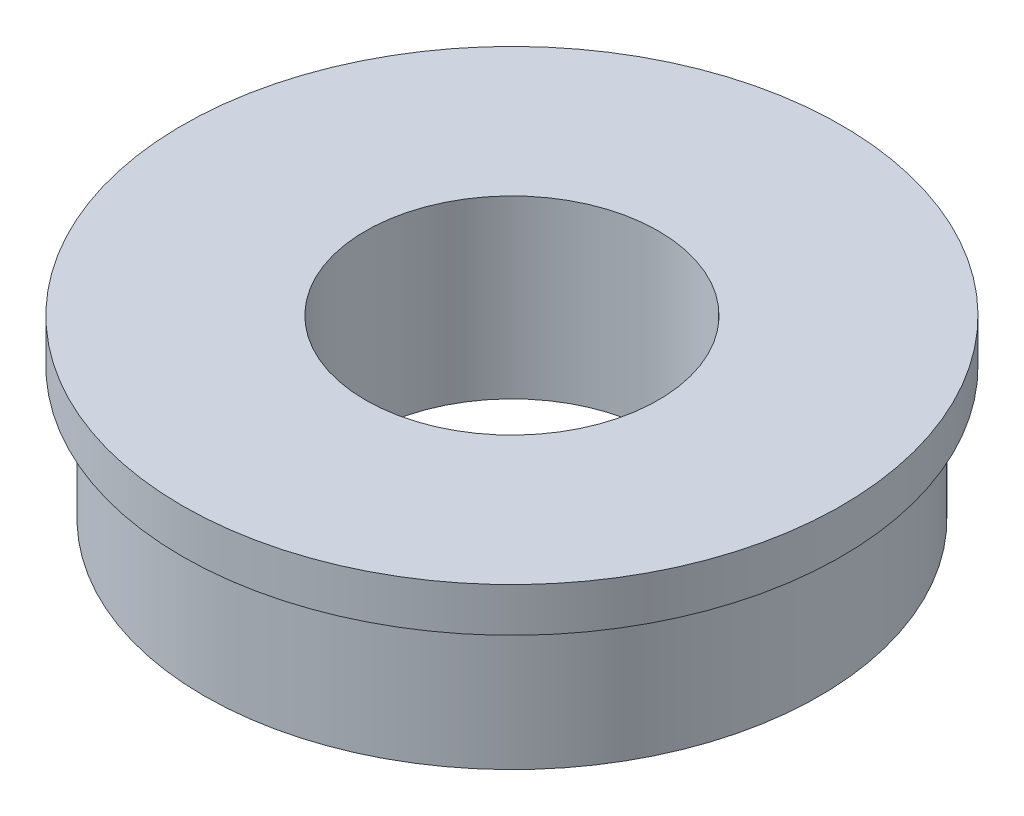
SolidWorks part; units mm, degrees
ref_plane "前视基准面" through (0, 0, 0) normal (0, 0, 1) x (1, 0, 0)
ref_plane "上视基准面" through (0, 0, 0) normal (0, 1, 0) x (1, 0, 0)
ref_plane "右视基准面" through (0, 0, 0) normal (1, 0, 0) x (0, 0, -1)
sketch "Sketch1" plane through (0, 0, 0) normal (0, 1, 0) x (1, 0, 0)
  circle A0 centre (0, 0) radius 10
  circle A1 centre (0, 0) radius 21
extrude "Boss-Extrude1" add sketch "Sketch1" along normal blind 9
sketch "Sketch2" plane through (0, 9, 0) normal (0, 1, 0) x (1, 0, 0)
  circle A0 centre (0, 0) radius 10
  circle A1 centre (0, 0) radius 22.5
extrude "Boss-Extrude2" add sketch "Sketch2" along normal blind 3
